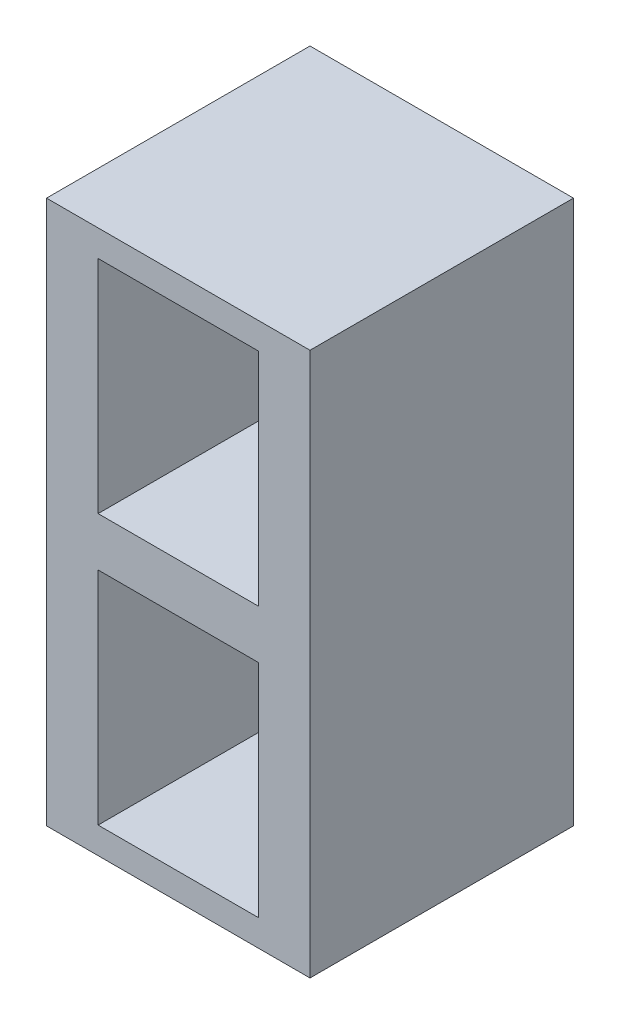
SolidWorks part; units mm, degrees
ref_plane "Front Plane" through (0, 0, 0) normal (0, 0, 1) x (1, 0, 0)
ref_plane "Top Plane" through (0, 0, 0) normal (0, 1, 0) x (1, 0, 0)
ref_plane "Right Plane" through (0, 0, 0) normal (1, 0, 0) x (0, 0, -1)
sketch "Sketch1" plane through (0, 0, 0) normal (0, 1, 0) x (1, 0, 0)
  line L1 (94.5, 94.5) -> (-94.5, 94.5)
  line L2 (94.5, 94.5) -> (94.5, -94.5)
  line L3 (94.5, -94.5) -> (-94.5, -94.5)
  line L4 (-94.5, 94.5) -> (-94.5, -94.5)
  dimension "D1" = 94.5
  dimension "D2" = 94.5
  dimension "D3" = 94.5
  dimension "D4" = 94.5
extrude "Boss-Extrude1" add sketch "Sketch1" along normal blind 390
sketch "Sketch2" plane through (0, 0, 94.5) normal (0, 0, 1) x (1, 0, 0)
  line L0 (-94.5, 390) -> (-94.5, 0) construction
  line L1 (-57.5, 371) -> (57.5, 371)
  line L2 (-57.5, 371) -> (-57.5, 212.5)
  line L3 (-57.5, 212.5) -> (57.5, 212.5)
  line L4 (57.5, 371) -> (57.5, 212.5)
  line L5 (94.5, 390) -> (94.5, 0) construction
  line L6 (-94.5, 390) -> (94.5, 390) construction
  line L7 (94.5, 195) -> (-94.5, 195) construction
  line L8 (57.5, 19) -> (57.5, 177.5)
  line L9 (-57.5, 177.5) -> (57.5, 177.5)
  line L10 (-57.5, 19) -> (-57.5, 177.5)
  line L11 (-57.5, 19) -> (57.5, 19)
  dimension "D1" = 37
  dimension "D2" = 37
  dimension "D3" = 19
  dimension "D4" = 17.5
extrude "Cut-Extrude1" cut sketch "Sketch2" against normal through all
